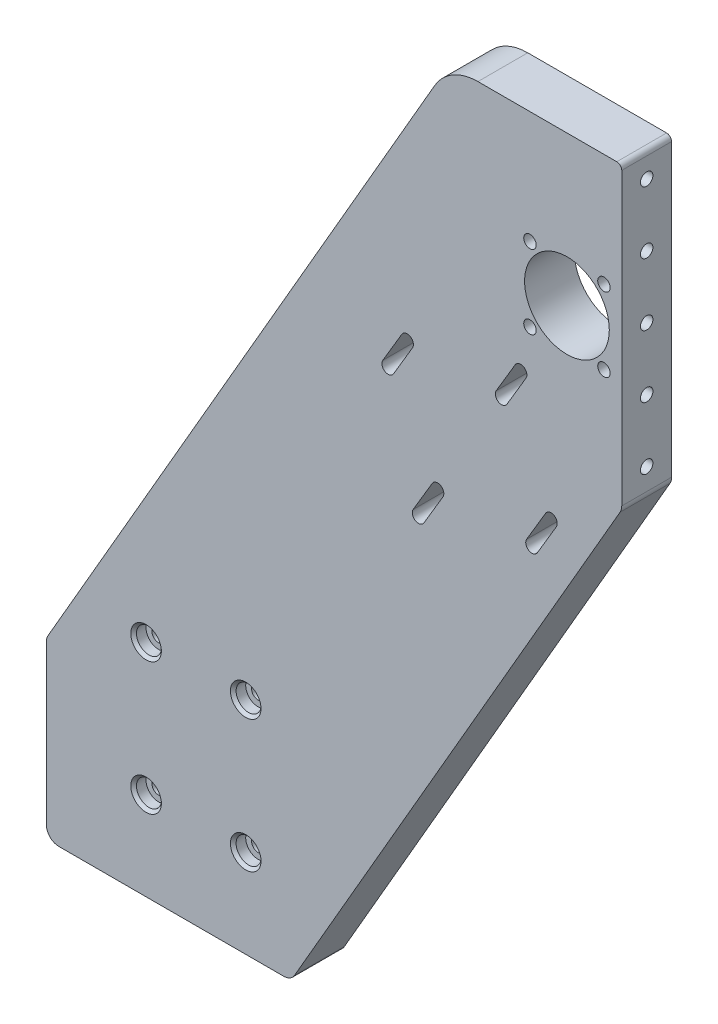
SolidWorks part; units mm, degrees
ref_plane "Piano frontale" through (0, 0, 0) normal (0, 0, 1) x (1, 0, 0)
ref_plane "Piano superiore" through (0, 0, 0) normal (0, 1, 0) x (1, 0, 0)
ref_plane "Piano destro" through (0, 0, 0) normal (1, 0, 0) x (0, 0, -1)
sketch "Schizzo1" plane through (0, 0, 0) normal (0, 0, 1) x (1, 0, 0)
  line L0 (5, 0) -> (95.2628, 0)
  line L1 (99.5929, 2.5) -> (230.2702, 228.8397)
  line L2 (230.9401, 231.3397) -> (230.9401, 348)
  line L3 (228.9401, 350) -> (173.2051, 350)
  line L4 (0, 68.6603) -> (0, 5)
  line L5 (155.8846, 340) -> (0.6699, 71.1603)
  line L9 (208.9401, 290) -> (194.0909, 304.8492) construction
  line L10 (208.9401, 290) -> (187.9401, 290) construction
  line L11 (208.9401, 290) -> (208.9401, 311) construction
  line L12 (50.1314, 0) -> (50.1314, 156.8301) construction
  circle A4 centre (208.9401, 290) radius 17
  circle A5 centre (208.9401, 290) radius 21 construction
  arc A6 (99.5929, 2.5) -> (95.2628, 0) centre (95.2628, 5) cw
  arc A7 (5, 0) -> (0, 5) centre (5, 5) cw
  arc A8 (0, 68.6603) -> (0.6699, 71.1603) centre (5, 68.6603) cw
  arc A9 (230.9401, 231.3397) -> (230.2702, 228.8397) centre (225.9401, 231.3397) cw
  arc A10 (230.9401, 348) -> (228.9401, 350) centre (228.9401, 348) ccw
  arc A11 (173.2051, 350) -> (155.8846, 340) centre (173.2051, 330) ccw
  circle A14 centre (223.7894, 304.8492) radius 2.5
  circle A15 centre (223.7894, 275.1508) radius 2.5
  circle A18 centre (194.0909, 275.1508) radius 2.5
  circle A19 centre (194.0909, 304.8492) radius 2.5
  point P27 (194.0909, 304.8492)
  point P28 (223.7894, 304.8492)
  point P29 (223.7894, 275.1508)
  point P30 (194.0909, 275.1508)
  point P31 (230.9401, 350)
  point P39 (0, 0)
  point P42 (0, 70)
  point P45 (230.9401, 230)
  point P48 (230.9401, 350)
  dimension "D6" = 60
  dimension "D9" = 34
  dimension "D11" = 45
  dimension "D14" = 5
  dimension "D15" = 5
  dimension "D17" = 42
  dimension "D12" = 2
  dimension "D1" = 120
  dimension "D2" = 120
  dimension "D3" = 70
  dimension "D4" = 350
  dimension "D5" = 120
  dimension "D10" = 22
extrude "Estrusione-Estrusione2" add sketch "Schizzo1" against normal blind 20
sketch "Sketch1" plane through (0, 0, 0) normal (0, -1, 0) x (1, 0, 0)
  line L0 (5, -10) -> (95.2628, -10) construction
  line L1 (5, -20) -> (5, 0) construction
  line L2 (95.2628, -20) -> (95.2628, 0) construction
  line L3 (50.1314, 0) -> (50.1314, -20) construction
  line L4 (5, 0) -> (95.2628, 0) construction
  line L5 (5, -20) -> (95.2628, -20) construction
  point P12 (50.1314, -10)
  point P13 (85.1314, -10)
  point P14 (15.1314, -10)
  dimension "D1" = 35
hole_wizard "M5 Tapped Hole1" positions "3DSketch1" profile "Sketch2" tap size "M5" standard "ISO"
sketch3d "3DSketch1"
  point P0 (50.1314, 0, -10)
  point P3 (85.1314, 0, -10)
  point P6 (15.1314, 0, -10)
sketch "Sketch2" plane through (50.1314, 0, -10) normal (1, 0, 0) x (0, 0, -1)
  line L0 (0, 0) -> (0, 18.6618)
  line L1 (0, 18.6618) -> (2.1, 17.4)
  line L2 (2.1, 17.4) -> (2.1, 0)
  line L5 (2.1, 0) -> (0, 0)
  line L10 (0, 18.6618) -> (-2.1, 17.4) construction
  line L11 (0, -6.35) -> (0, 107.95) construction
  dimension "Tap Drill Dia." = 4.2
  dimension "Tap Drill Depth" = 17.4
  dimension "Drill Angle" = 118
sketch "Sketch3" plane through (0, 0, 0) normal (0, 0, 1) x (1, 0, 0)
  line L0 (0, 68.6603) -> (0, 5) construction
  point P0 (40, 88.5)
  point P1 (80, 88.5)
  point P2 (80, 35.5)
  point P3 (40, 35.5)
  dimension "D1" = 40
  dimension "D2" = 53
  dimension "D3" = 40
hole_wizard "CBORE for M5 SHCS1" positions "3DSketch3" profile "Sketch5" counterbore size "M5" standard "ANSI Metric" end condition through all
sketch3d "3DSketch3"
  point P0 (80, 88.5, 0)
  point P3 (80, 35.5, 0)
  point P6 (40, 35.5, 0)
  point P9 (40, 88.5, 0)
sketch "Sketch5" plane through (80, 88.5, 0) normal (1, 0, 0) x (0, -1, 0)
  line L0 (0, 0) -> (0, 20)
  line L1 (0, 20) -> (2.65, 20)
  line L3 (2.65, 20) -> (2.65, 5)
  line L4 (5, 5) -> (2.65, 5)
  line L5 (5, 5) -> (5, 1.145)
  line L6 (5, 1.145) -> (6.145, 0)
  line L7 (6.145, 0) -> (0, 0)
  line L8 (-5, 1.145) -> (-6.145, 0) construction
  line L11 (0, -6.35) -> (0, 107.95) construction
  dimension "Thru Hole Dia." = 5.3
  dimension "Thru Hole Depth" = 20
  dimension "C'Bore Dia." = 10
  dimension "C'Bore Depth" = 5
  dimension "Near C'Sink Dia." = 12.29
  dimension "Near C'Sink Angle" = 90
sketch "Sketch7" plane through (230.9401, 0, 0) normal (1, 0, 0) x (0, 0, -1)
  point P0 (10, 340)
  point P1 (10, 315)
  point P2 (10, 290)
  point P3 (10, 265)
  point P4 (10, 240)
hole_wizard "M6 Tapped Hole1" positions "3DSketch6" profile "Sketch12" tap size "M6" standard "ISO"
sketch3d "3DSketch6"
  point P0 (230.9401, 340, -10)
  point P3 (230.9401, 315, -10)
  point P6 (230.9401, 290, -10)
  point P9 (230.9401, 265, -10)
  point P12 (230.9401, 240, -10)
sketch "Sketch12" plane through (230.9401, 340, -10) normal (0, 1, 0) x (0, 0, -1)
  line L0 (0, 0) -> (0, 20.5022)
  line L1 (0, 20.5022) -> (2.5, 19)
  line L2 (2.5, 19) -> (2.5, 0)
  line L5 (2.5, 0) -> (0, 0)
  line L10 (0, 20.5022) -> (-2.5, 19) construction
  line L11 (0, -6.35) -> (0, 107.95) construction
  dimension "Tap Drill Dia." = 5
  dimension "Tap Drill Depth" = 19
  dimension "Drill Angle" = 118
sketch "Sketch19" plane through (0, 0, 0) normal (0, 0, 1) x (1, 0, 0)
  line L0 (182.692, 244.9178) -> (190.3485, 257.8166) construction
  line L1 (180.5422, 246.1939) -> (188.1987, 259.0927)
  line L2 (184.8418, 243.6417) -> (192.4983, 256.5405)
  line L3 (194.8927, 199.3841) -> (202.5492, 212.2828) construction
  line L4 (192.7429, 200.6602) -> (200.3994, 213.5589)
  line L5 (197.0425, 198.108) -> (204.699, 211.0067)
  line L6 (149.359, 186.9838) -> (157.0155, 199.8825) construction
  line L7 (147.2092, 188.2599) -> (154.8657, 201.1586)
  line L8 (151.5088, 185.7077) -> (159.1653, 198.6065)
  line L9 (137.1582, 232.7171) -> (144.8148, 245.6158) construction
  line L10 (135.0084, 233.9932) -> (142.665, 246.8919)
  line L11 (139.308, 231.441) -> (146.9645, 244.3398)
  arc A0 (180.5422, 246.1939) -> (184.8418, 243.6417) centre (182.692, 244.9178) ccw
  arc A1 (192.4983, 256.5405) -> (188.1987, 259.0927) centre (190.3485, 257.8166) ccw
  arc A2 (192.7429, 200.6602) -> (197.0425, 198.108) centre (194.8927, 199.3841) ccw
  arc A3 (204.699, 211.0067) -> (200.3994, 213.5589) centre (202.5492, 212.2828) ccw
  arc A4 (147.2092, 188.2599) -> (151.5088, 185.7077) centre (149.359, 186.9838) ccw
  arc A5 (159.1653, 198.6065) -> (154.8657, 201.1586) centre (157.0155, 199.8825) ccw
  arc A6 (135.0084, 233.9932) -> (139.308, 231.441) centre (137.1582, 232.7171) ccw
  arc A7 (146.9645, 244.3398) -> (142.665, 246.8919) centre (144.8148, 245.6158) ccw
  point P0 (186.5202, 251.3672)
  point P1 (140.9865, 239.1665)
  point P2 (153.1872, 193.4332)
  point P3 (198.721, 205.8335)
  point P6 (186.5202, 251.3672)
  point P13 (198.721, 205.8335)
  point P20 (153.1872, 193.4332)
  point P27 (140.9865, 239.1665)
  dimension "D1" = 5
  dimension "D2" = 15
extrude "Cut-Extrude1" cut sketch "Sketch19" against normal through all
